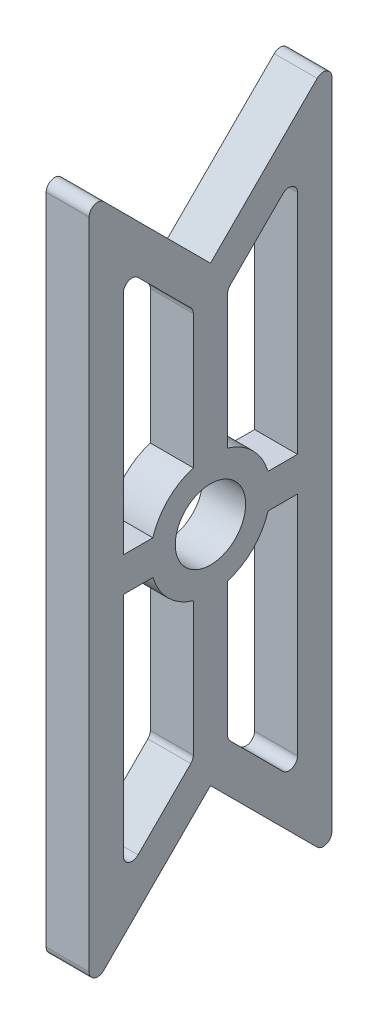
SolidWorks part; units mm, degrees
ref_plane "Front Plane" through (0, 0, 0) normal (0, 0, 1) x (1, 0, 0)
ref_plane "Top Plane" through (0, 0, 0) normal (0, 1, 0) x (1, 0, 0)
ref_plane "Right Plane" through (0, 0, 0) normal (1, 0, 0) x (0, 0, -1)
sketch "Sketch1" plane through (0, 0, 0) normal (1, 0, 0) x (0, 0, -1)
  line L0 (14.1421, 0) -> (14.1421, -81) construction
  line L1 (0, 0) -> (28.2843, 0)
  line L2 (0, 0) -> (0, -81)
  line L3 (0, -81) -> (28.2843, -81)
  line L4 (28.2843, 0) -> (28.2843, -81)
  line L5 (0, 0) -> (14.1421, -14.1421)
  line L6 (14.1421, -14.1421) -> (28.2843, 0)
  line L7 (0, -40.5) -> (28.2843, -40.5) construction
  line L8 (14.1421, -66.8579) -> (28.2843, -81)
  line L9 (0, -81) -> (14.1421, -66.8579)
  dimension "D1" = 45
  dimension "D2" = 20
  dimension "D3" = 81
extrude "Boss-Extrude1" add sketch "Sketch1" along normal blind 5 contours L2 L9 L8 L4 L6 L5
sketch "Sketch2" plane through (5, 0, 0) normal (1, 0, 0) x (0, 0, -1)
  line L6 (14.1421, -14.1421) -> (14.1421, -66.8579) construction
  line L8 (12.1421, -65.5) -> (16.1421, -65.5)
  line L9 (12.1421, -65.5) -> (12.1421, -15.5)
  line L10 (12.1421, -15.5) -> (16.1421, -15.5)
  line L11 (16.1421, -65.5) -> (16.1421, -15.5)
  line L12 (4, -9.6569) -> (4, -71.3431)
  line L13 (4, -71.3431) -> (14.1421, -61.201)
  line L14 (14.1421, -61.201) -> (24.2843, -71.3431)
  line L15 (24.2843, -71.3431) -> (24.2843, -9.6569)
  line L16 (24.2843, -9.6569) -> (14.1421, -19.799)
  line L17 (14.1421, -19.799) -> (4, -9.6569)
  line L18 (4, -9.6569) -> (4, -71.3431)
  line L19 (4, -71.3431) -> (14.1421, -61.201)
  line L20 (14.1421, -61.201) -> (24.2843, -71.3431)
  line L21 (24.2843, -71.3431) -> (24.2843, -9.6569)
  line L22 (24.2843, -9.6569) -> (14.1421, -19.799)
  line L23 (14.1421, -19.799) -> (4, -9.6569)
  line L24 (12.1421, -65.5) -> (16.1421, -15.5) construction
  line L25 (12.1421, -15.5) -> (16.1421, -65.5) construction
  point P3 (14.1421, -40.5)
  dimension "D2" = 50
  dimension "D3" = 4
  dimension "D1" = 4
extrude "Cut-Extrude1" cut sketch "Sketch2" against normal through all contours L9 L23 L18 L19 | L21 L22 L11 L20
sketch "Sketch6" plane through (5, 0, 0) normal (1, 0, 0) x (0, 0, -1)
  line L0 (28.2843, -40.5) -> (0, -40.5) construction
  line L1 (28.2843, 0) -> (28.2843, -81) construction
  line L2 (0, 0) -> (0, -81) construction
  line L3 (14.1421, -14.1421) -> (14.1421, -66.8579) construction
  line L4 (24.2843, -71.3431) -> (24.2843, -9.6569) construction
  line L5 (4, -38.5) -> (24.2843, -38.5)
  line L6 (4, -38.5) -> (4, -42.5)
  line L7 (4, -42.5) -> (24.2843, -42.5)
  line L8 (24.2843, -38.5) -> (24.2843, -42.5)
  line L9 (4, -38.5) -> (24.2843, -42.5) construction
  line L10 (4, -42.5) -> (24.2843, -38.5) construction
  circle A0 centre (14.1421, -40.5) radius 7
  point P14 (14.1421, -40.5)
  line M2 (24.2843, -9.6569) -> (24.2843, -71.3431)
  line M4 (16.1421, -63.201) -> (16.1421, -17.799)
  line M6 (12.1421, -17.799) -> (12.1421, -63.201)
  line M8 (4, -71.3431) -> (4, -9.6569)
  dimension "D1" = 14
  dimension "D5" = 4
extrude "Boss-Extrude2" add sketch "Sketch6" against normal through all contours A0 L7 M4 | L7 A0 L5 M4 | L5 A0 M4 | A0 L5 M6 | L7 A0 M6 | L5 A0 L7 M6 | A0 L5 L7 M8 | A0 L7 L5 M2
sketch "Sketch7" plane through (5, 0, 0) normal (1, 0, 0) x (0, 0, -1)
  circle A0 centre (14.1421, -40.5) radius 4.1
  dimension "D1" = 8.2
extrude "Cut-Extrude2" cut sketch "Sketch7" against normal through all
fillet "Fillet1" radius 1 12 edges at (2.5, -63.201, -12.1421) (2.5, -63.201, -16.1421) (2.5, -17.799, -16.1421) (2.5, -17.799, -12.1421) (2.5, -9.6569, -4) (2.5, -9.6569, -24.2843) (2.5, -71.3431, -4) (2.5, -71.3431, -24.2843) (2.5, -81, -28.2843) (2.5, -81, 0) (2.5, 0, 0) (2.5, 0, -28.2843)
